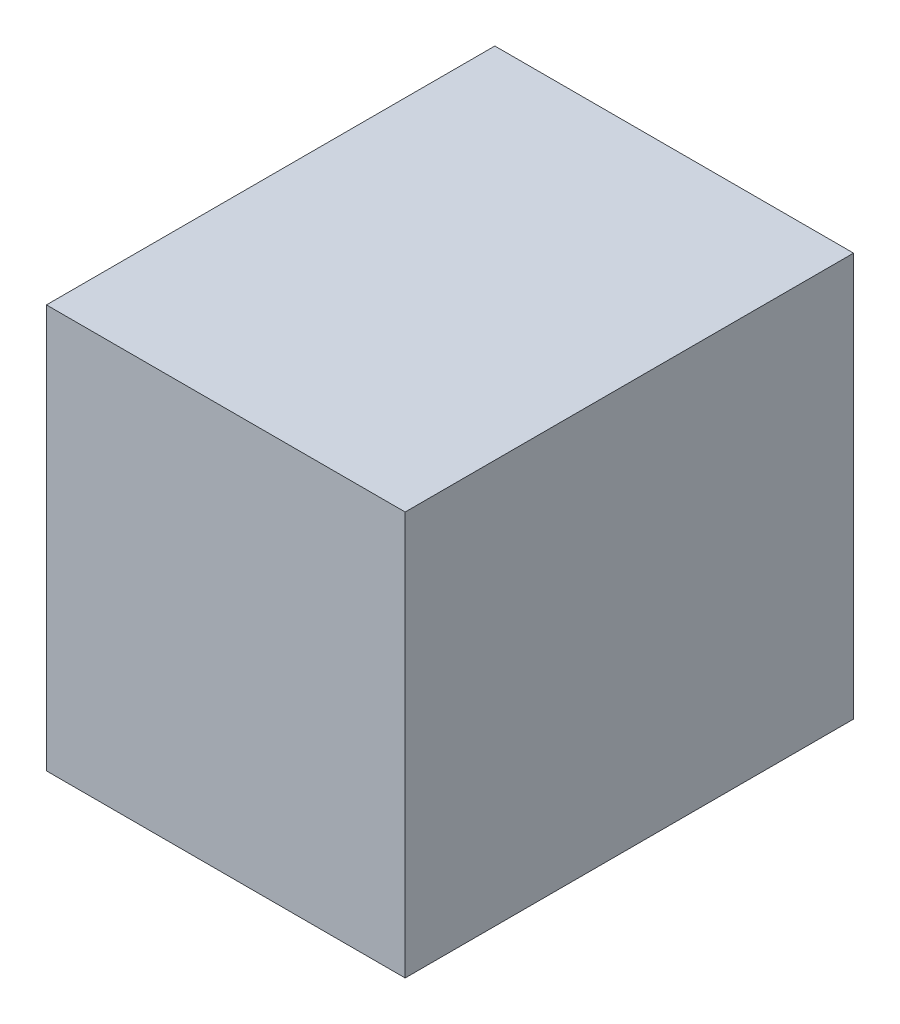
SolidWorks part; units mm, degrees
material "ｱｸﾘﾙ (中-上級の耐衝撃性)"
ref_plane "正面" through (0, 0, 0) normal (0, 0, 1) x (1, 0, 0)
ref_plane "平面" through (0, 0, 0) normal (0, 1, 0) x (1, 0, 0)
ref_plane "右側面" through (0, 0, 0) normal (1, 0, 0) x (0, 0, -1)
sketch "ｽｹｯﾁ1" plane through (0, 0, 0) normal (0, 0, 1) x (1, 0, 0)
  line L1 (0, 0) -> (400, 0)
  line L2 (0, 0) -> (0, 450)
  line L3 (0, 450) -> (400, 450)
  line L4 (400, 0) -> (400, 450)
  dimension "D1" = 400
  dimension "D2" = 450
extrude "ﾎﾞｽ - 押し出し1" add sketch "ｽｹｯﾁ1" along normal blind 500
